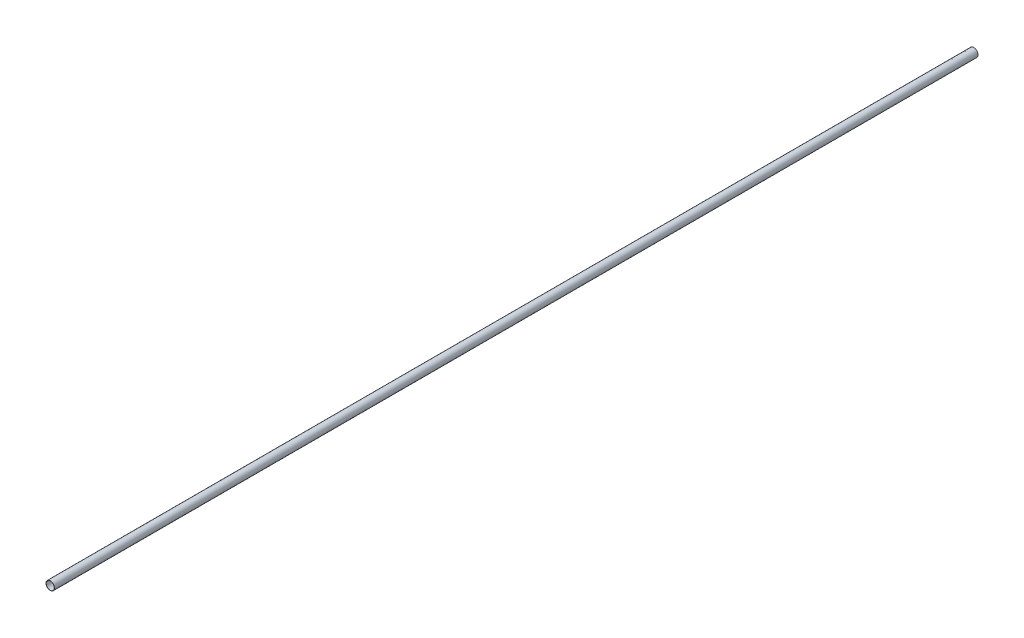
SolidWorks part; units mm, degrees
ref_plane "Front Plane" through (0, 0, 0) normal (0, 0, 1) x (1, 0, 0)
ref_plane "Top Plane" through (0, 0, 0) normal (0, 1, 0) x (1, 0, 0)
ref_plane "Right Plane" through (0, 0, 0) normal (1, 0, 0) x (0, 0, -1)
ref_plane "Plane1"
sketch "Sketch1" plane through (0, 0, 0) normal (0, 0, 1) x (1, 0, 0)
  circle A0 centre (0.1401, 0) radius 55
  circle A1 centre (0.1401, 0) radius 52.7
  dimension "D1" = 110
extrude "Extrusion1" add sketch "Sketch1" along normal blind 12000 contours A0 A1
